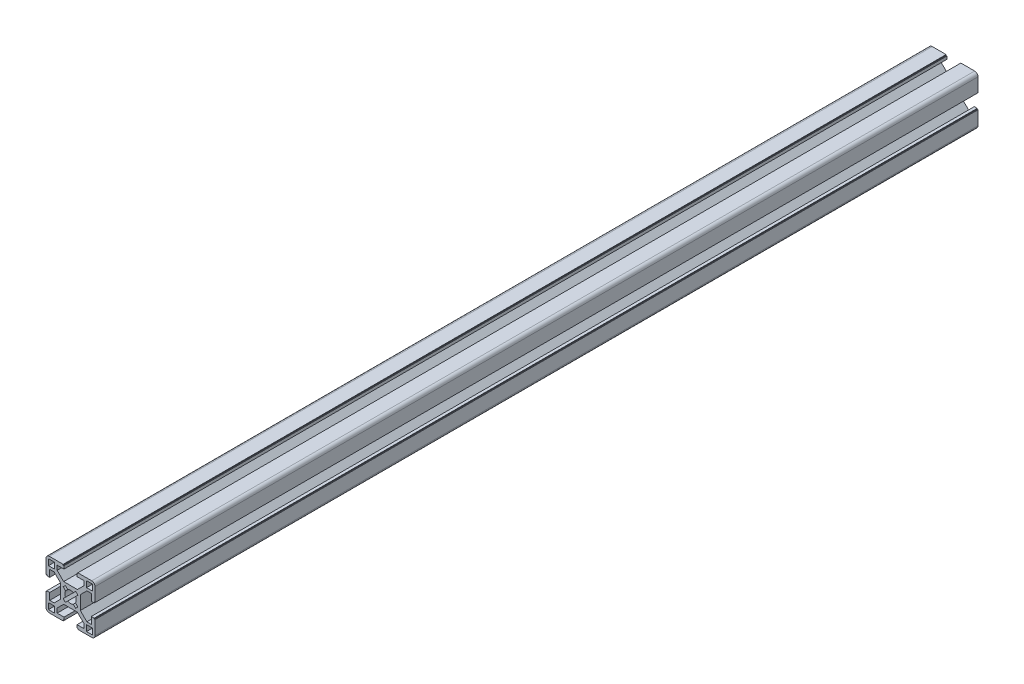
SolidWorks part; units mm, degrees
ref_plane "Front Plane" through (0, 0, 0) normal (0, 0, 1) x (1, 0, 0)
ref_plane "Top Plane" through (0, 0, 0) normal (0, 1, 0) x (1, 0, 0)
ref_plane "Right Plane" through (0, 0, 0) normal (1, 0, 0) x (0, 0, -1)
sketch "Sketch1" plane through (0, 0, 0) normal (0, 0, 1) x (1, 0, 0)
  line L0 (-15, 0) -> (15, 0) construction
  line L1 (0, -15) -> (0, 15) construction
  line L2 (-4.5, 15) -> (4.5, 15) construction
  line L3 (-4, -15) -> (4, -15) construction
  line L4 (-4.5, 15) -> (-4.5, 14.5)
  line L5 (-4.5, 14.5) -> (-4, 14.5)
  line L6 (-4, 14.5) -> (-4, 12.71)
  line L7 (-4, 12.71) -> (-8.2, 12.71)
  line L8 (-8.2, 12.71) -> (-8.2, 9.9961)
  line L9 (-8.2, 9.9961) -> (-4.2039, 6)
  line L10 (-4.2039, 6) -> (0, 6)
  line L11 (0, 0) -> (-15, 15) construction
  line L12 (-4.5, 15) -> (-12.968, 15)
  line L13 (-4.4937, 3.1431) -> (-3.1431, 4.4937)
  line L14 (-13.47, 9.79) -> (-9.79, 9.79)
  line L15 (-13.47, 9.79) -> (-13.47, 13.47)
  line L16 (-13.47, 13.47) -> (-9.79, 13.47)
  line L17 (-9.79, 9.79) -> (-9.79, 13.47)
  line L18 (-13.47, 9.79) -> (-9.79, 13.47) construction
  line L19 (-13.47, 13.47) -> (-9.79, 9.79) construction
  line L20 (-3.1431, 4.4937) -> (-1.7057, 3.0563)
  line L21 (-4.4937, 3.1431) -> (-3.0563, 1.7057)
  line L22 (-6, 4.2039) -> (-6, 0)
  line L23 (-9.9961, 8.2) -> (-6, 4.2039)
  line L24 (-15, 4.5) -> (-15, 12.968)
  line L25 (-12.71, 8.2) -> (-9.9961, 8.2)
  line L26 (-12.71, 4) -> (-12.71, 8.2)
  line L27 (-14.5, 4) -> (-12.71, 4)
  line L28 (-14.5, 4.5) -> (-14.5, 4)
  line L29 (-15, 4.5) -> (-14.5, 4.5)
  circle A0 centre (0, 0) radius 3.5
  arc A1 (-12.968, 15) -> (-15, 12.968) centre (-12.968, 12.968) ccw
  point P4 (0, 0)
  point P8 (0, 0)
  point P13 (0, 15)
  point P15 (0, -15)
  point P16 (0, 6)
  point P23 (-11.63, 11.63)
  point P26 (0, 6)
  point P33 (-3.8184, 3.8184)
  dimension "Center Hole Diameter" = 7
  dimension "D11" = 2.032
  dimension "Rail Height" = 30
  dimension "Rail Width" = 30
  dimension "T-Slot Width" = 8
  dimension "T-Slot Depth" = 9
  dimension "D1" = 9
  dimension "D2" = 45
  dimension "D3" = 8
  dimension "D4" = 2.29
  dimension "D5" = 16.4
  dimension "D7" = 2.54
  dimension "D6" = 3.37
  dimension "D8" = 3.68
  dimension "D9" = 5.4
  dimension "D10" = 1.91
sketch "Sketch2" plane through (0, 0, 0) normal (1, 0, 0) x (0, 0, -1)
  line L0 (-1219.2, 0) -> (1219.2, 0) construction
  line L2 (0, -15) -> (0, 15) construction
  line L3 (0, -15) -> (0, 15) construction
  line L4 (-1219.2, -15) -> (-1219.2, 15) construction
  line L5 (1219.2, -15) -> (1219.2, 15) construction
  point P0 (-1181.7, 0)
  point P3 (0, 0)
  point P4 (1181.7, 0)
  point P12 (-1219.2, 0)
  point P14 (1219.2, 0)
  dimension "Length" = 2438.4
  dimension "D1" = 37.5
sketch "Sketch3" plane through (0, 0, 0) normal (0, 0, 1) x (1, 0, 0)
  line L0 (-3.1431, 4.4937) -> (-1.7057, 3.0563) construction
  line L1 (-4.4937, 3.1431) -> (-3.1431, 4.4937) construction
  line L2 (-4.4937, 3.1431) -> (-3.0563, 1.7057) construction
  line L4 (-13.47, 9.79) -> (-9.79, 9.79)
  line L5 (-9.79, 9.79) -> (-9.79, 13.47)
  line L6 (-9.79, 13.47) -> (-13.47, 13.47)
  line L7 (-13.47, 13.47) -> (-13.47, 9.79)
  line L8 (-13.47, 9.79) -> (-9.79, 9.79)
  line L9 (-9.79, 9.79) -> (-9.79, 13.47)
  line L10 (-9.79, 13.47) -> (-13.47, 13.47)
  line L11 (-13.47, 13.47) -> (-13.47, 9.79)
  line L12 (-4.2039, 6) -> (0, 6) construction
  line L13 (-8.2, 9.9961) -> (-4.2039, 6) construction
  line L14 (-8.2, 12.71) -> (-8.2, 9.9961) construction
  line L15 (-4, 12.71) -> (-8.2, 12.71) construction
  line L16 (-4, 14.5) -> (-4, 12.71) construction
  line L17 (-4.5, 14.5) -> (-4, 14.5) construction
  line L18 (-4.5, 15) -> (-4.5, 14.5) construction
  line L19 (-4.5, 15) -> (-12.968, 15) construction
  line L20 (-15, 4.5) -> (-15, 12.968) construction
  line L21 (-15, 4.5) -> (-14.5, 4.5) construction
  line L22 (-14.5, 4.5) -> (-14.5, 4) construction
  line L23 (-14.5, 4) -> (-12.71, 4) construction
  line L24 (-12.71, 4) -> (-12.71, 8.2) construction
  line L25 (-12.71, 8.2) -> (-9.9961, 8.2) construction
  line L26 (-9.9961, 8.2) -> (-6, 4.2039) construction
  line L27 (-6, 4.2039) -> (-6, 0) construction
  line L28 (-3.1431, 4.4937) -> (-1.7057, 3.0563)
  line L29 (-4.4937, 3.1431) -> (-3.1431, 4.4937)
  line L30 (-4.4937, 3.1431) -> (-3.0563, 1.7057)
  line L32 (-4.2039, 6) -> (0, 6)
  line L33 (-8.2, 9.9961) -> (-4.2039, 6)
  line L34 (-8.2, 12.71) -> (-8.2, 9.9961)
  line L35 (-4, 12.71) -> (-8.2, 12.71)
  line L36 (-4, 14.5) -> (-4, 12.71)
  line L37 (-4.5, 14.5) -> (-4, 14.5)
  line L38 (-4.5, 15) -> (-4.5, 14.5)
  line L39 (-4.5, 15) -> (-12.968, 15)
  line L40 (-15, 4.5) -> (-15, 12.968)
  line L41 (-15, 4.5) -> (-14.5, 4.5)
  line L42 (-14.5, 4.5) -> (-14.5, 4)
  line L43 (-14.5, 4) -> (-12.71, 4)
  line L44 (-12.71, 4) -> (-12.71, 8.2)
  line L45 (-12.71, 8.2) -> (-9.9961, 8.2)
  line L46 (-9.9961, 8.2) -> (-6, 4.2039)
  line L47 (-6, 4.2039) -> (-6, 0)
  line L48 (9.79, 13.47) -> (9.79, 9.79)
  line L49 (9.79, 9.79) -> (13.47, 9.79)
  line L50 (13.47, 9.79) -> (13.47, 13.47)
  line L51 (13.47, 13.47) -> (9.79, 13.47)
  line L52 (4.4937, 3.1431) -> (3.0563, 1.7057)
  line L53 (3.1431, 4.4937) -> (4.4937, 3.1431)
  line L54 (3.1431, 4.4937) -> (1.7057, 3.0563)
  line L55 (6, 4.2039) -> (6, 0)
  line L56 (9.9961, 8.2) -> (6, 4.2039)
  line L57 (12.71, 8.2) -> (9.9961, 8.2)
  line L58 (12.71, 4) -> (12.71, 8.2)
  line L59 (14.5, 4) -> (12.71, 4)
  line L60 (14.5, 4.5) -> (14.5, 4)
  line L61 (15, 4.5) -> (14.5, 4.5)
  line L62 (15, 4.5) -> (15, 12.968)
  line L63 (4.5, 15) -> (12.968, 15)
  line L64 (4.5, 15) -> (4.5, 14.5)
  line L65 (4.5, 14.5) -> (4, 14.5)
  line L66 (4, 14.5) -> (4, 12.71)
  line L67 (4, 12.71) -> (8.2, 12.71)
  line L68 (8.2, 12.71) -> (8.2, 9.9961)
  line L69 (8.2, 9.9961) -> (4.2039, 6)
  line L70 (4.2039, 6) -> (0, 6)
  line L71 (13.47, -9.79) -> (9.79, -9.79)
  line L72 (9.79, -9.79) -> (9.79, -13.47)
  line L73 (9.79, -13.47) -> (13.47, -13.47)
  line L74 (13.47, -13.47) -> (13.47, -9.79)
  line L75 (3.1431, -4.4937) -> (1.7057, -3.0563)
  line L76 (4.4937, -3.1431) -> (3.1431, -4.4937)
  line L77 (4.4937, -3.1431) -> (3.0563, -1.7057)
  line L78 (4.2039, -6) -> (0, -6)
  line L79 (8.2, -9.9961) -> (4.2039, -6)
  line L80 (8.2, -12.71) -> (8.2, -9.9961)
  line L81 (4, -12.71) -> (8.2, -12.71)
  line L82 (4, -14.5) -> (4, -12.71)
  line L83 (4.5, -14.5) -> (4, -14.5)
  line L84 (4.5, -15) -> (4.5, -14.5)
  line L85 (4.5, -15) -> (12.968, -15)
  line L86 (15, -4.5) -> (15, -12.968)
  line L87 (15, -4.5) -> (14.5, -4.5)
  line L88 (14.5, -4.5) -> (14.5, -4)
  line L89 (14.5, -4) -> (12.71, -4)
  line L90 (12.71, -4) -> (12.71, -8.2)
  line L91 (12.71, -8.2) -> (9.9961, -8.2)
  line L92 (9.9961, -8.2) -> (6, -4.2039)
  line L93 (6, -4.2039) -> (6, 0)
  line L94 (-9.79, -13.47) -> (-9.79, -9.79)
  line L95 (-9.79, -9.79) -> (-13.47, -9.79)
  line L96 (-13.47, -9.79) -> (-13.47, -13.47)
  line L97 (-13.47, -13.47) -> (-9.79, -13.47)
  line L98 (-4.4937, -3.1431) -> (-3.0563, -1.7057)
  line L99 (-3.1431, -4.4937) -> (-4.4937, -3.1431)
  line L100 (-3.1431, -4.4937) -> (-1.7057, -3.0563)
  line L101 (-6, -4.2039) -> (-6, 0)
  line L102 (-9.9961, -8.2) -> (-6, -4.2039)
  line L103 (-12.71, -8.2) -> (-9.9961, -8.2)
  line L104 (-12.71, -4) -> (-12.71, -8.2)
  line L105 (-14.5, -4) -> (-12.71, -4)
  line L106 (-14.5, -4.5) -> (-14.5, -4)
  line L107 (-15, -4.5) -> (-14.5, -4.5)
  line L108 (-15, -4.5) -> (-15, -12.968)
  line L109 (-4.5, -15) -> (-12.968, -15)
  line L110 (-4.5, -15) -> (-4.5, -14.5)
  line L111 (-4.5, -14.5) -> (-4, -14.5)
  line L112 (-4, -14.5) -> (-4, -12.71)
  line L113 (-4, -12.71) -> (-8.2, -12.71)
  line L114 (-8.2, -12.71) -> (-8.2, -9.9961)
  line L115 (-8.2, -9.9961) -> (-4.2039, -6)
  line L116 (-4.2039, -6) -> (0, -6)
  arc A0 (-12.968, 15) -> (-15, 12.968) centre (-12.968, 12.968) ccw construction
  circle A1 centre (0, 0) radius 3.5
  arc A2 (-3.0563, 1.7057) -> (-3.0563, -1.7057) centre (0, 0) ccw
  arc A3 (-12.968, 15) -> (-15, 12.968) centre (-12.968, 12.968) ccw
  arc A4 (15, 12.968) -> (12.968, 15) centre (12.968, 12.968) ccw
  arc A5 (12.968, -15) -> (15, -12.968) centre (12.968, -12.968) ccw
  arc A6 (-15, -12.968) -> (-12.968, -15) centre (-12.968, -12.968) ccw
  arc A7 (1.7057, 3.0563) -> (-1.7057, 3.0563) centre (0, 0) ccw
  arc A8 (3.0563, -1.7057) -> (3.0563, 1.7057) centre (0, 0) ccw
  arc A9 (-1.7057, -3.0563) -> (1.7057, -3.0563) centre (0, 0) ccw
  point P116 (0, 0)
  dimension "D1" = 0
  dimension "D2" = 0
  dimension "D3" = 4
extrude "Boss-Extrude1" add sketch "Sketch3" along normal mid plane 2438.4
sketch "Sketch4" plane through (0, 15, 0) normal (0, 1, 0) x (1, 0, 0)
  line L0 (15, -1219.2) -> (15, 1219.2) construction
  line L1 (-15, 1219.2) -> (15, 1219.2)
  line L2 (-15, 1219.2) -> (-15, -679.2)
  line L3 (-15, -679.2) -> (15, -679.2)
  line L4 (15, 1219.2) -> (15, -679.2)
  line L5 (12.968, -1219.2) -> (4.5, -1219.2) construction
  dimension "D1" = 540
extrude "Cut-Extrude1" cut sketch "Sketch4" against normal through all
equation "\"D1@Sketch2\" = \"Rail Height@Sketch1\" * 1.25"
equation "\"D1@Sketch1\"=\"T-Slot Width@Sketch1\"+1mm"
equation "\"D3@Sketch1\"=\"T-Slot Width@Sketch1\""
equation "\"D1@Boss-Extrude1\"=\"Length@Sketch2\""
